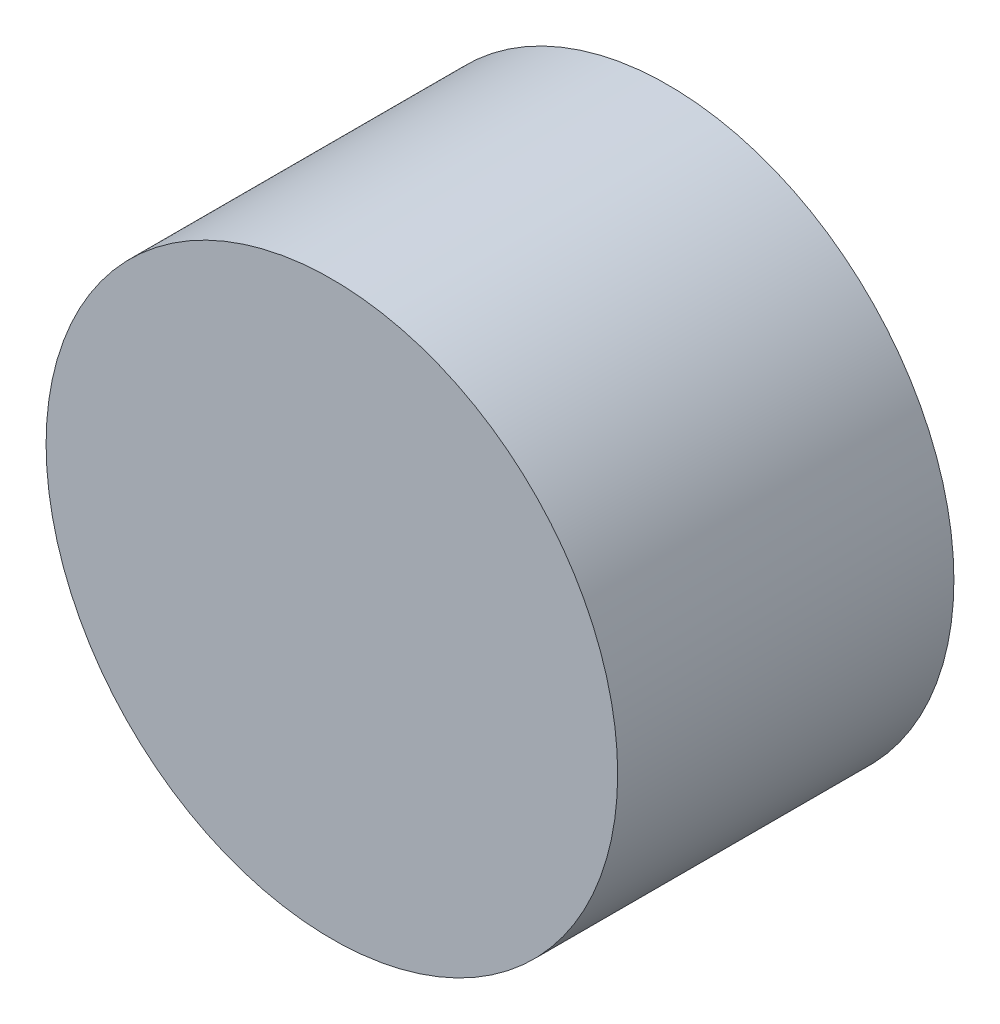
SolidWorks part; units mm, degrees
ref_plane "前视基准面" through (0, 0, 0) normal (0, 0, 1) x (1, 0, 0)
ref_plane "上视基准面" through (0, 0, 0) normal (0, 1, 0) x (1, 0, 0)
ref_plane "右视基准面" through (0, 0, 0) normal (1, 0, 0) x (0, 0, -1)
sketch "草图1" plane through (0, 0, 0) normal (0, 0, 1) x (1, 0, 0)
  circle A0 centre (0, 0) radius 1.7
extrude "凸台-拉伸1" add sketch "草图1" along normal blind 2
